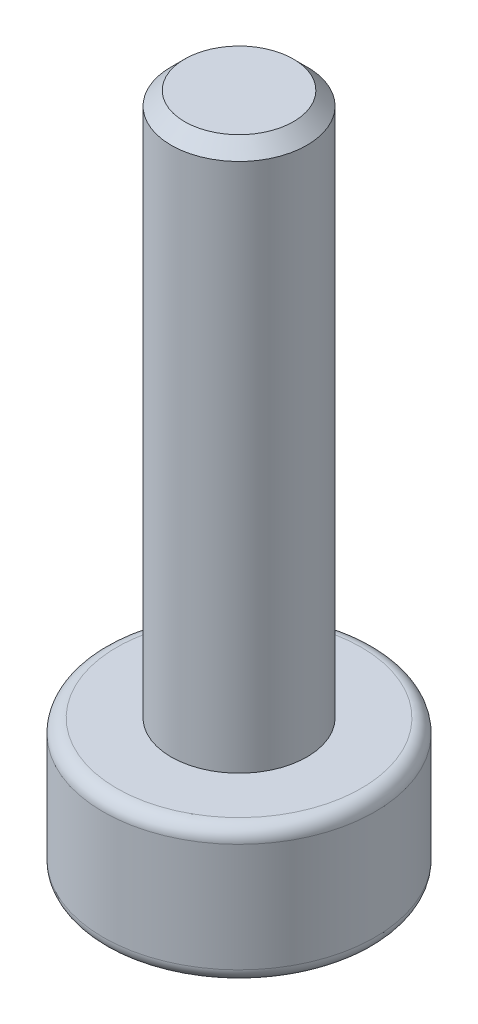
SolidWorks part; units mm, degrees
material "AISI 304"
ref_plane "前视基准面" through (0, 0, 0) normal (0, 0, 1) x (1, 0, 0)
ref_plane "上视基准面" through (0, 0, 0) normal (0, 1, 0) x (1, 0, 0)
ref_plane "右视基准面" through (0, 0, 0) normal (1, 0, 0) x (0, 0, -1)
sketch "草图2" plane through (0, 0, 0) normal (0, 1, 0) x (1, 0, 0)
  circle A0 centre (0, 0) radius 2
  dimension "D1" = 4
extrude "凸台-拉伸1" add sketch "草图2" along normal blind 2
sketch "草图3" plane through (0, 2, 0) normal (0, 1, 0) x (1, 0, 0)
  circle A0 centre (0, 0) radius 1
  dimension "D1" = 2
extrude "凸台-拉伸2" add sketch "草图3" along normal blind 8
fillet "圆角1" radius 0.2 2 edges at (0, 2, 2) (0, 0, 2)
sketch "草图4" plane through (0, 0, 0) normal (0, -1, 0) x (1, 0, 0)
  circle A0 centre (0, 0) radius 0.765
  dimension "D1" = 1.53
extrude "切除-拉伸1" cut sketch "草图4" against normal blind 1.52
chamfer "倒角1" distance 0.1 angle 45 1 edges at (0, 0, -0.765)
chamfer "倒角2" distance 0.2 angle 45 1 edges at (0, 10, 1)
